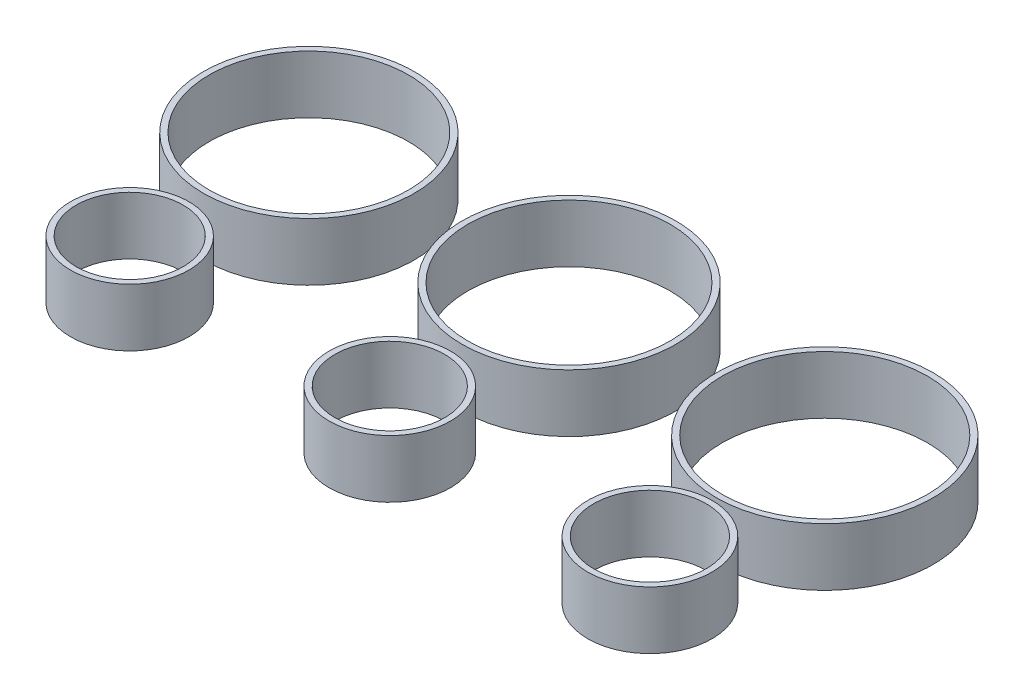
SolidWorks part; units mm, degrees
ref_plane "Front Plane" through (0, 0, 0) normal (0, 0, 1) x (1, 0, 0)
ref_plane "Top Plane" through (0, 0, 0) normal (0, 1, 0) x (1, 0, 0)
ref_plane "Right Plane" through (0, 0, 0) normal (1, 0, 0) x (0, 0, -1)
sketch "Sketch1" plane through (0, 0, 0) normal (0, 1, 0) x (1, 0, 0)
  circle A0 centre (0, 0) radius 18.25
  dimension "D1" = 36.5
extrude "Boss-Extrude1" add sketch "Sketch1" along normal blind 10
sketch "Sketch2" plane through (0, 10, 0) normal (0, 1, 0) x (1, 0, 0)
  circle A0 centre (0, 0) radius 17.25
  dimension "D1" = 34.5
extrude "Cut-Extrude1" cut sketch "Sketch2" against normal blind 10
sketch "Sketch3" plane through (0, 0, 0) normal (0, 1, 0) x (1, 0, 0)
  circle A0 centre (45, 0) radius 18.5
  circle A1 centre (0, 0) radius 18.25 construction
  dimension "D1" = 45
  dimension "D2" = 37
extrude "Boss-Extrude2" add sketch "Sketch3" along normal blind 10 separate body
sketch "Sketch4" plane through (0, 10, 0) normal (0, 1, 0) x (1, 0, 0)
  circle A0 centre (45, 0) radius 17.5
  dimension "D1" = 35
extrude "Cut-Extrude2" cut sketch "Sketch4" against normal blind 10
sketch "Sketch5" plane through (0, 0, 0) normal (0, 1, 0) x (1, 0, 0)
  circle A0 centre (90, -0.7405) radius 18.75
  dimension "D1" = 90
  dimension "D2" = 37.5
extrude "Boss-Extrude3" add sketch "Sketch5" along normal blind 10 separate body
sketch "Sketch6" plane through (0, 0, 0) normal (0, -1, 0) x (1, 0, 0)
  circle A0 centre (90, 0.7405) radius 17.75
  dimension "D1" = 35.5
extrude "Cut-Extrude3" cut sketch "Sketch6" against normal blind 10
sketch "Sketch7" plane through (0, 0, 0) normal (0, 1, 0) x (1, 0, 0)
  line L0 (0, -31) -> (90, -31) construction
  line L1 (90, -31) -> (90, -0.7405) construction
  line L2 (90, -0.7405) -> (0, 0) construction
  line L3 (0, 0) -> (0, -31) construction
  circle A0 centre (0, -31) radius 10.25
  circle A1 centre (45, -31) radius 10.5
  circle A2 centre (90, -31) radius 10.75
  dimension "D2" = 20.5
  dimension "D3" = 21
  dimension "D4" = 21.5
  dimension "D1" = 31
extrude "Boss-Extrude4" add sketch "Sketch7" along normal blind 10 separate body
sketch "Sketch8" plane through (0, 0, 0) normal (0, 1, 0) x (1, 0, 0)
  circle A0 centre (0, -31) radius 9.25
  circle A1 centre (45, -31) radius 9.5
  circle A2 centre (90, -31) radius 9.75
  dimension "D1" = 18.5
  dimension "D2" = 19
  dimension "D3" = 19.5
extrude "Cut-Extrude5" cut sketch "Sketch8" along normal blind 10
